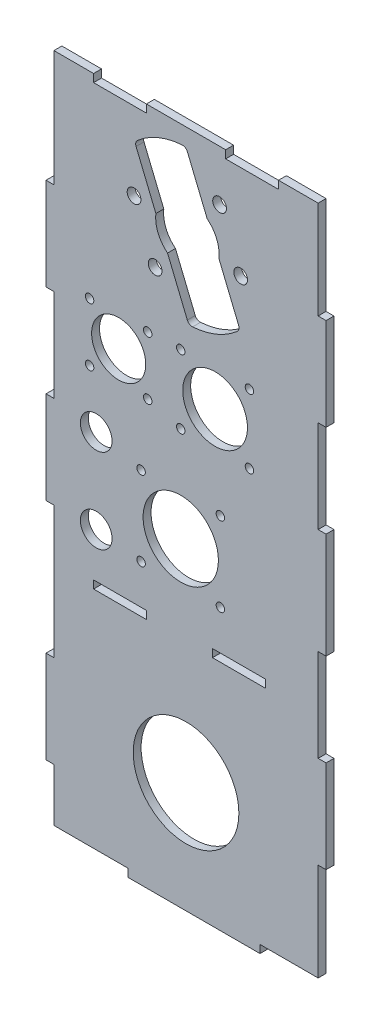
SolidWorks part; units mm, degrees
ref_plane "Front Plane" through (0, 0, 0) normal (0, 0, 1) x (1, 0, 0)
ref_plane "Top Plane" through (0, 0, 0) normal (0, 1, 0) x (1, 0, 0)
ref_plane "Right Plane" through (0, 0, 0) normal (1, 0, 0) x (0, 0, -1)
sketch "Sketch1" plane through (0, 0, 0) normal (0, 0, 1) x (1, 0, 0)
  line L1 (-50, 127) -> (50, 127)
  line L2 (-50, 127) -> (-50, -127)
  line L3 (-50, -127) -> (50, -127)
  line L4 (50, 127) -> (50, -127)
  dimension "D1" = 254
  dimension "D2" = 100
  dimension "D3" = 50
  dimension "D4" = 127
extrude "Boss-Extrude1" add sketch "Sketch1" along normal blind 3
sketch "Sketch2" plane through (50, 0, 0) normal (1, 0, 0) x (0, 0, -1)
  line L0 (0, -127) -> (0, 127) construction
  line L1 (0, 90) -> (-3, 90)
  line L2 (0, 90) -> (0, 55)
  line L3 (0, 55) -> (-3, 55)
  line L4 (-3, 90) -> (-3, 55)
  line L5 (0, 90) -> (-3, 90) construction
  line L6 (-3, -127) -> (-3, 127) construction
  line L7 (0, 55) -> (-3, 55) construction
  line L8 (0, 20) -> (-3, 20) construction
  line L9 (0, 20) -> (-3, 20)
  line L10 (0, 20) -> (0, -20)
  line L11 (0, -20) -> (-3, -20)
  line L12 (-3, 20) -> (-3, -20)
  line L13 (0, -20) -> (-3, -20) construction
  line L14 (0, -55) -> (-3, -55) construction
  line L15 (0, -55) -> (-3, -55)
  line L16 (0, -55) -> (0, -90)
  line L17 (0, -90) -> (-3, -90)
  line L18 (-3, -55) -> (-3, -90)
  line L19 (0, -90) -> (-3, -90) construction
extrude "Boss-Extrude2" add sketch "Sketch2" along normal blind 3
sketch "Sketch3" plane through (0, 127, 0) normal (0, 1, 0) x (1, 0, 0)
  line L0 (50, 0) -> (-50, 0) construction
  line L1 (35, 0) -> (15, 0)
  line L2 (35, 0) -> (35, -3)
  line L3 (35, -3) -> (15, -3)
  line L4 (15, 0) -> (15, -3)
  line L5 (35, -3) -> (35, 0) construction
  line L6 (50, -3) -> (-50, -3) construction
  line L7 (15, 0) -> (15, -3) construction
  line L8 (-15, -3) -> (-15, 0) construction
  line L9 (-15, 0) -> (-35, 0)
  line L10 (-15, 0) -> (-15, -3)
  line L11 (-15, -3) -> (-35, -3)
  line L12 (-35, 0) -> (-35, -3)
  line L13 (-35, 0) -> (-35, -3) construction
extrude "Cut-Extrude1" cut sketch "Sketch3" against normal blind 3
sketch "Sketch4" plane through (0, 0, 3) normal (0, 0, 1) x (1, 0, 0)
  line L1 (-35, -39) -> (-15, -39)
  line L2 (-35, -39) -> (-35, -42)
  line L3 (-35, -42) -> (-15, -42)
  line L4 (-15, -39) -> (-15, -42)
  line L5 (10, -39) -> (30, -39)
  line L6 (10, -39) -> (10, -42)
  line L7 (10, -42) -> (30, -42)
  line L8 (30, -39) -> (30, -42)
extrude "Cut-Extrude2" cut sketch "Sketch4" against normal blind 3
sketch "Sketch5" plane through (0, 0, 3) normal (0, 0, 1) x (1, 0, 0)
  line L0 (-40, 56) -> (-11, 56) construction
  line L1 (-40, 56) -> (-40, 27) construction
  line L2 (-50, 127) -> (-50, -127) construction
  line L3 (-50, -127) -> (-22, -127) construction
  line L16 (-40, 27) -> (-11, 27) construction
  line L17 (-11, 56) -> (-11, 27) construction
  line L18 (-20, 9) -> (16, 9) construction
  line L19 (-20, 9) -> (-20, -27) construction
  line L20 (-20, -27) -> (16, -27) construction
  line L21 (16, 9) -> (16, -27) construction
  line L22 (-50, -130) -> (-22, -130) construction
  line L23 (-5, 56) -> (27, 56) construction
  line L24 (-5, 56) -> (-5, 24) construction
  line L25 (-5, 24) -> (27, 24) construction
  line L26 (27, 56) -> (27, 24) construction
  line L27 (8.0037, 100.8645) -> (0.511, 119.0973)
  line L28 (19.9128, 71.8849) -> (12.4201, 90.1176)
  line L29 (-7.0037, 82.1355) -> (0.489, 63.9027)
  line L30 (-18.9128, 111.1151) -> (-11.4201, 92.8824)
  line L31 (20.6776, 88.4399) -> (12.6955, 107.8637) construction
  line L32 (12.6955, 107.8637) -> (-19.6776, 94.5601) construction
  line L33 (-19.6776, 94.5601) -> (-11.6955, 75.1363) construction
  line L34 (16.6865, 98.1518) -> (-15.6865, 84.8482) construction
  line L35 (-35, 127) -> (-50, 127) construction
  circle A0 centre (0, -88) radius 20
  circle A16 centre (-25.5, 41.5) radius 10.25
  circle A17 centre (-36.5, 52.5) radius 1.6
  circle A18 centre (-14.5, 52.5) radius 1.6
  circle A19 centre (-36.5, 30.5) radius 1.6
  circle A20 centre (-14.5, 30.5) radius 1.6
  circle A21 centre (-17, 6) radius 1.6
  circle A22 centre (13, 6) radius 1.6
  circle A23 centre (-17, -24) radius 1.6
  circle A24 centre (13, -24) radius 1.6
  circle A25 centre (-2, -9) radius 14.25
  circle A26 centre (11, 40) radius 12.25
  circle A27 centre (-2, 53) radius 1.6
  circle A28 centre (24, 53) radius 1.6
  circle A29 centre (24, 27) radius 1.6
  circle A30 centre (-2, 27) radius 1.6
  circle A31 centre (0.5, 91.5) radius 32.5 construction
  arc A32 (12.4201, 90.1176) -> (8.0037, 100.8645) centre (0.5, 91.5) ccw
  arc A33 (19.3687, 69.6098) -> (19.9128, 71.8849) centre (18.0629, 71.1247) ccw
  arc A34 (2.4756, 62.6676) -> (19.3687, 69.6098) centre (0.5, 91.5) ccw
  arc A35 (0.489, 63.9027) -> (2.4756, 62.6676) centre (2.3388, 64.6629) ccw
  arc A36 (-11.4201, 92.8824) -> (-7.0037, 82.1355) centre (0.5, 91.5) ccw
  arc A37 (-18.3687, 113.3902) -> (-18.9128, 111.1151) centre (-17.0629, 111.8753) ccw
  arc A38 (-1.4756, 120.3324) -> (-18.3687, 113.3902) centre (0.5, 91.5) ccw
  arc A39 (0.511, 119.0973) -> (-1.4756, 120.3324) centre (-1.3388, 118.3371) ccw
  circle A40 centre (-19.6776, 94.5601) radius 2.6
  circle A41 centre (-11.6955, 75.1363) radius 2.6
  circle A42 centre (12.6955, 107.8637) radius 2.6
  circle A43 centre (20.6776, 88.4399) radius 2.6
  circle A44 centre (-34, 10) radius 6
  circle A45 centre (-34, -22) radius 6
  dimension "D1" = 40
  dimension "D2" = 30
  dimension "D3" = 19
  dimension "D4" = 29
  dimension "D5" = 20.5
  dimension "D6" = 14.5
  dimension "D7" = 14.5
  dimension "D10" = 3.2
  dimension "D19" = 36
  dimension "D22" = 18
  dimension "D23" = 15
  dimension "D24" = 15
  dimension "D25" = 30
  dimension "D33" = 3.2
  dimension "D38" = 13
  dimension "D39" = 13
  dimension "D40" = 15
  dimension "D41" = 45
  dimension "D11" = 3.2
  dimension "D14" = 3.2
  dimension "D15" = 3.2
  dimension "D16" = 3.2
  dimension "D18" = 28.5
  dimension "D29" = 24.5
  dimension "D32" = 3.2
  dimension "D34" = 3.2
  dimension "D35" = 3.2
  dimension "D45" = 32.5
  dimension "D46" = 12
  dimension "D47" = 12
  dimension "D55" = 3
  dimension "D56" = 18
  dimension "D57" = 108
  dimension "D58" = 10
  dimension "D59" = 12
  dimension "D60" = 12
  dimension "D61" = 20
  dimension "D8" = 22
  dimension "D9" = 22
  dimension "D12" = 11
  dimension "D13" = 11
  dimension "D17" = 30
  dimension "D20" = 36
  dimension "D21" = 18
  dimension "D26" = 103
  dimension "D27" = 32
  dimension "D28" = 32
  dimension "D30" = 16
  dimension "D31" = 16
  dimension "D36" = 26
  dimension "D37" = 26
  dimension "D42" = 6
  dimension "D43" = 0
  dimension "D44" = 29
  dimension "D48" = 35
  dimension "D49" = 21
  dimension "D50" = 21
  dimension "D51" = 35
  dimension "D52" = 19.7123
  dimension "D53" = 19.7123
  dimension "D54" = 19.7123
extrude "Cut-Extrude3" cut sketch "Sketch5" against normal blind 3
sketch "Sketch6" plane through (0, -127, 0) normal (0, -1, 0) x (1, 0, 0)
  line L0 (-50, 0) -> (50, 0) construction
  line L1 (28, 0) -> (-22, 0)
  line L2 (28, 0) -> (28, 3)
  line L3 (28, 3) -> (-22, 3)
  line L4 (-22, 0) -> (-22, 3)
  line L5 (-50, 3) -> (50, 3) construction
  line L6 (53, 3) -> (53, 0) construction
  dimension "D1" = 50
  dimension "D2" = 25
extrude "Boss-Extrude3" add sketch "Sketch6" along normal blind 3
sketch "Sketch7" plane through (0, 0, 3) normal (0, 0, 1) x (1, 0, 0)
  circle A2 centre (40, -63.9246) radius 3
  circle A3 centre (40, -27.9246) radius 3
  dimension "D1" = 6
  dimension "D3" = 6
sketch "Sketch8" plane through (-50, 0, 0) normal (-1, 0, 0) x (0, 0, 1)
  line L0 (3, 127) -> (3, -127) construction
  line L1 (3, -107) -> (0, -107)
  line L2 (3, -107) -> (3, -72)
  line L3 (3, -72) -> (0, -72)
  line L4 (0, -107) -> (0, -72)
  line L5 (0, -107) -> (3, -107) construction
  line L6 (0, 127) -> (0, -127) construction
  line L7 (3, -72) -> (0, -72) construction
  line L8 (0, -22) -> (3, -22) construction
  line L9 (3, -22) -> (0, -22)
  line L10 (3, -22) -> (3, 13)
  line L11 (3, 13) -> (0, 13)
  line L12 (0, -22) -> (0, 13)
  line L13 (3, 13) -> (0, 13) construction
  line L14 (0, 48) -> (3, 48) construction
  line L15 (3, 48) -> (0, 48)
  line L16 (3, 48) -> (3, 83)
  line L17 (3, 83) -> (0, 83)
  line L18 (0, 48) -> (0, 83)
  line L19 (3, 83) -> (0, 83) construction
extrude "Boss-Extrude4" add sketch "Sketch8" along normal blind 3
